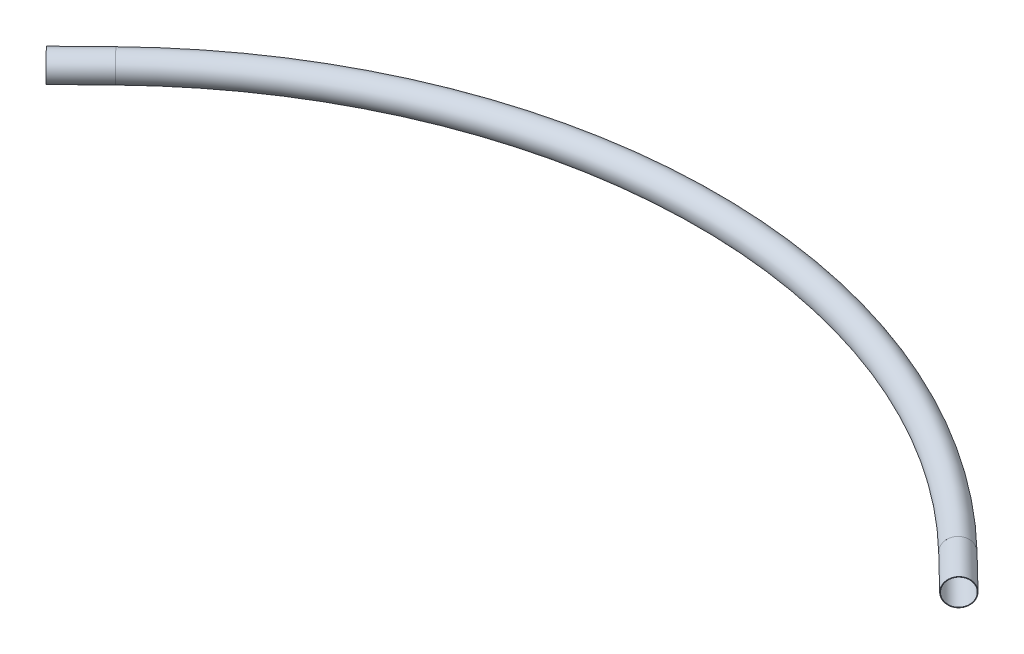
SolidWorks part; units mm, degrees
ref_plane "Front Plane" through (0, 0, 0) normal (0, 0, 1) x (1, 0, 0)
ref_plane "Top Plane" through (0, 0, 0) normal (0, 1, 0) x (1, 0, 0)
ref_plane "Right Plane" through (0, 0, 0) normal (1, 0, 0) x (0, 0, -1)
sketch "Pipe_Definition" plane through (0, 0, 0) normal (0, 1, 0) x (1, 0, 0)
  line L0 (0, 0) -> (0, 1060.45) construction
  line L1 (-2611.4375, 0) -> (2611.4375, 0) construction
  line L6 (-2611.4375, 0) -> (-2829.9441, -212.5039)
  line L10 (2611.4375, 0) -> (2829.9441, -212.5039)
  arc A1 (2611.4375, 0) -> (-2611.4375, 0) centre (0, -2685.2052) ccw
  dimension "D1" = 304.8
  dimension "D3" = 5222.875
  dimension "D4" = 2818.5386
  dimension "D5" = 5659.8883
  dimension "D2" = 1060.45
  dimension "D6" = 2611.4375
other "Structural Member1"
ref_plane "Plane1" through (2611.4375, 0, 0) normal (-0.7169, 0, -0.6972) x (-0.6972, 0, 0.7169)
sketch "Sketch12" plane through (2611.4375, 0, 0) normal (-0.7169, 0, -0.6972) x (-0.6972, 0, 0.7169)
  circle A0 centre (0, 0) radius 84.1375
  circle A1 centre (0, 0) radius 80.7339
  point P4 (0, 0)
  dimension "D1" = 168.275
  dimension "D2" = 161.4678
equation "\"D2@Sketch12\" = \"D1@Sketch12\" - .134*2"
